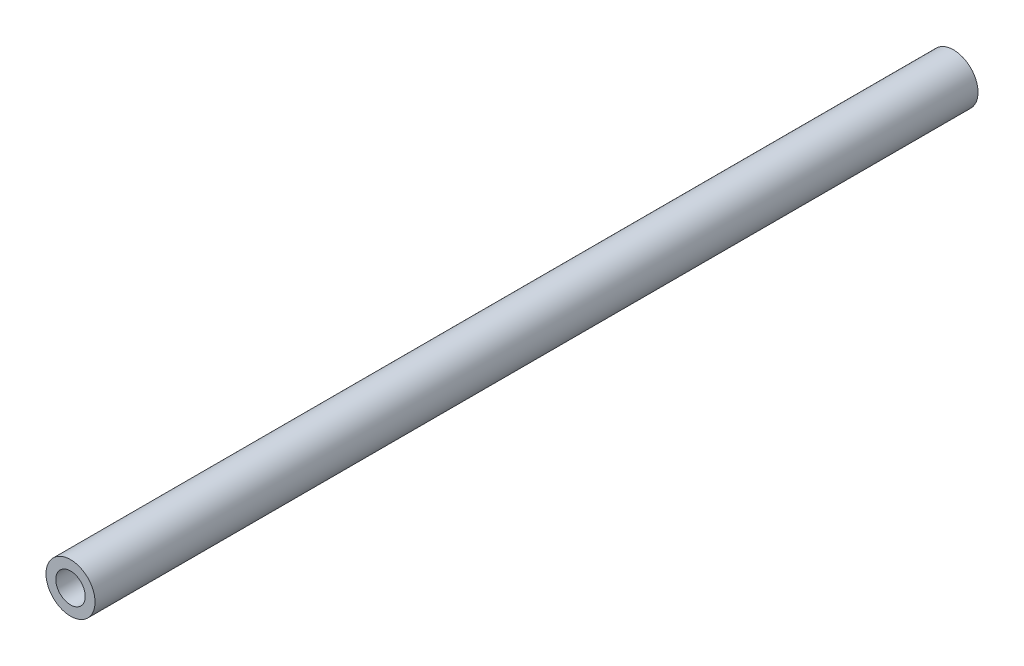
SolidWorks part; units mm, degrees
material "6061 合金"
ref_plane "前视基准面" through (0, 0, 0) normal (0, 0, 1) x (1, 0, 0)
ref_plane "上视基准面" through (0, 0, 0) normal (0, 1, 0) x (1, 0, 0)
ref_plane "右视基准面" through (0, 0, 0) normal (1, 0, 0) x (0, 0, -1)
sketch "草图1" plane through (0, 0, 0) normal (0, 0, 1) x (1, 0, 0)
  circle A0 centre (0, 0) radius 1.5
  circle A1 centre (0, 0) radius 2.5
  dimension "D1" = 3
  dimension "D2" = 5
extrude "凸台-拉伸1" add sketch "草图1" along normal blind 90
